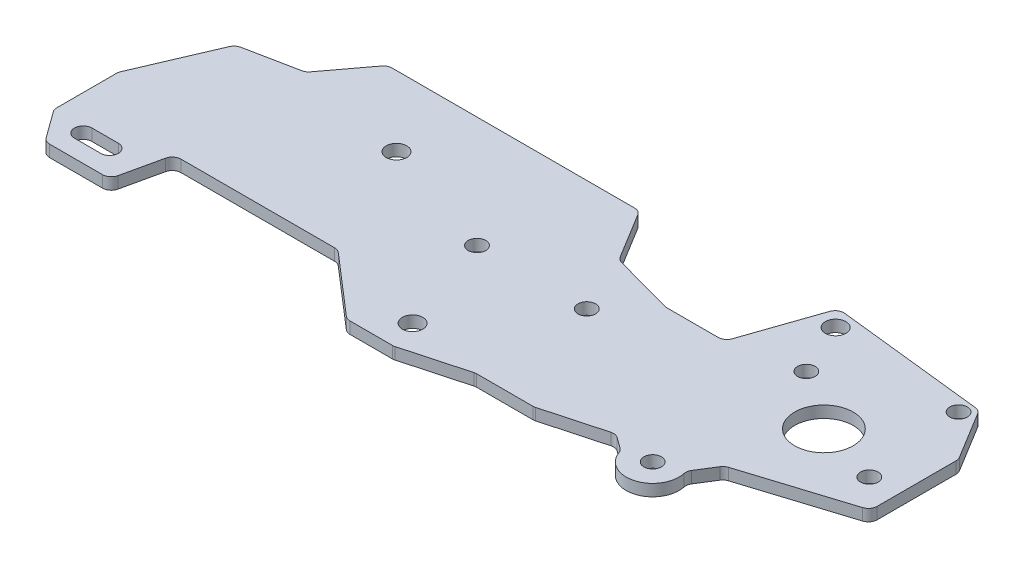
SolidWorks part; units mm, degrees
material "1060 Alloy"
ref_plane "Front Plane" through (0, 0, 0) normal (0, 0, 1) x (1, 0, 0)
ref_plane "Top Plane" through (0, 0, 0) normal (0, 1, 0) x (1, 0, 0)
ref_plane "Right Plane" through (0, 0, 0) normal (1, 0, 0) x (0, 0, -1)
sketch "Sketch1" plane through (0, 0, 0) normal (0, 1, 0) x (1, 0, 0)
  line L0 (0, 0) -> (43, 0)
  line L1 (43, 0) -> (48.5, -9)
  line L2 (48.5, -9) -> (59.5, -12)
  line L3 (59.5, -12) -> (69.5, -12)
  line L4 (69.5, -12) -> (74.5, 2.5)
  line L5 (74.5, 2.5) -> (101.5, -0.5)
  line L6 (101.5, -0.5) -> (107, -9.5)
  line L7 (107, -9.5) -> (107, -24.5)
  line L8 (107, -24.5) -> (88, -30.5)
  line L9 (88, -30.5) -> (85.5, -34.5)
  line L10 (0, 0) -> (-6, -8)
  line L11 (-6, -8) -> (-16, -10)
  line L12 (-16, -10) -> (-22, -24)
  line L13 (-22, -24) -> (-22, -35)
  line L14 (-22, -35) -> (-18, -40.5)
  line L15 (-18, -40.5) -> (-7, -40.5)
  line L16 (-7, -40.5) -> (-5, -31.5)
  line L17 (-5, -31.5) -> (23, -31.5)
  line L18 (23, -31.5) -> (34, -41)
  line L19 (34, -41) -> (42, -41)
  line L20 (42, -41) -> (53, -38)
  line L21 (53, -38) -> (63, -38)
  line L22 (63, -38) -> (74, -35)
  line L23 (74, -35) -> (76.8704, -37.0637)
  line L24 (-16, -34.5) -> (-11.5, -34.5)
  line L25 (-16, -37.5) -> (-11.5, -37.5)
  circle A0 centre (40.25, -36) radius 1.75
  circle A1 centre (81.25, -36) radius 1.5
  arc A2 (76.8704, -37.0637) -> (85.5, -34.5) centre (81.25, -36) ccw
  arc A3 (-11.5, -37.5) -> (-11.5, -34.5) centre (-11.5, -36) ccw
  arc A4 (-16, -34.5) -> (-16, -37.5) centre (-16, -36) ccw
  circle A5 centre (91, -16.5) radius 5
  circle A6 centre (77, -0.5) radius 1.75
  circle A7 centre (81, -9.5) radius 1.5
  circle A8 centre (100, -2.5) radius 1.5
  circle A9 centre (102, -19.75) radius 1.5
  circle A10 centre (53, -19) radius 1.5
  circle A11 centre (34.25, -19) radius 1.5
  circle A12 centre (13.5, -12) radius 1.75
  dimension "D39" = 3.5
  dimension "D40" = 5
  dimension "D41" = 6.25
  dimension "D42" = 3
  dimension "D43" = 41
  dimension "D44" = 6.5
  dimension "D45" = 6
  dimension "D46" = 10
  dimension "D47" = 16
  dimension "D48" = 8
  dimension "D49" = 3.5
  dimension "D50" = 3
  dimension "D51" = 2.5
  dimension "D52" = 3
  dimension "D53" = 1.5
  dimension "D54" = 1.5
  dimension "D55" = 4
  dimension "D56" = 9
  dimension "D57" = 3
  dimension "D58" = 7
  dimension "D59" = 2
  dimension "D60" = 3
  dimension "D61" = 5
  dimension "D62" = 17.25
  dimension "D63" = 3
  dimension "D64" = 16.5
  dimension "D65" = 7
  dimension "D66" = 3
  dimension "D67" = 18.75
  dimension "D68" = 3.5
  dimension "D69" = 12
  dimension "D70" = 20.75
  dimension "D1" = 43
  dimension "D2" = 9
  dimension "D3" = 5.5
  dimension "D4" = 11
  dimension "D5" = 3
  dimension "D6" = 10
  dimension "D7" = 14.5
  dimension "D8" = 5
  dimension "D9" = 27
  dimension "D10" = 3
  dimension "D11" = 5.5
  dimension "D12" = 9
  dimension "D13" = 15
  dimension "D14" = 19
  dimension "D15" = 6
  dimension "D16" = 2.5
  dimension "D17" = 4
  dimension "D18" = 6
  dimension "D19" = 8
  dimension "D20" = 10
  dimension "D21" = 2
  dimension "D22" = 14
  dimension "D23" = 6
  dimension "D24" = 11
  dimension "D25" = 5.5
  dimension "D26" = 4
  dimension "D27" = 11
  dimension "D28" = 9
  dimension "D29" = 2
  dimension "D30" = 28
  dimension "D31" = 9.5
  dimension "D32" = 11
  dimension "D33" = 8
  dimension "D34" = 3
  dimension "D35" = 11
  dimension "D36" = 10
  dimension "D37" = 3
  dimension "D38" = 11
extrude "Boss-Extrude1" add sketch "Sketch1" along normal blind 2
fillet "Fillet1" radius 1.5 25 edges at (85.5, 1, 34.5) (76.8704, 1, 37.0637) (74, 1, 35) (63, 1, 38) (53, 1, 38) (42, 1, 41) (34, 1, 41) (23, 1, 31.5) (-5, 1, 31.5) (-7, 1, 40.5) (-18, 1, 40.5) (-22, 1, 35) (-22, 1, 24) (-16, 1, 10) (-6, 1, 8) (0, 1, 0) (43, 1, 0) (48.5, 1, 9) (59.5, 1, 12) (69.5, 1, 12) (74.5, 1, -2.5) (101.5, 1, 0.5) (107, 1, 9.5) (107, 1, 24.5) (88, 1, 30.5)
